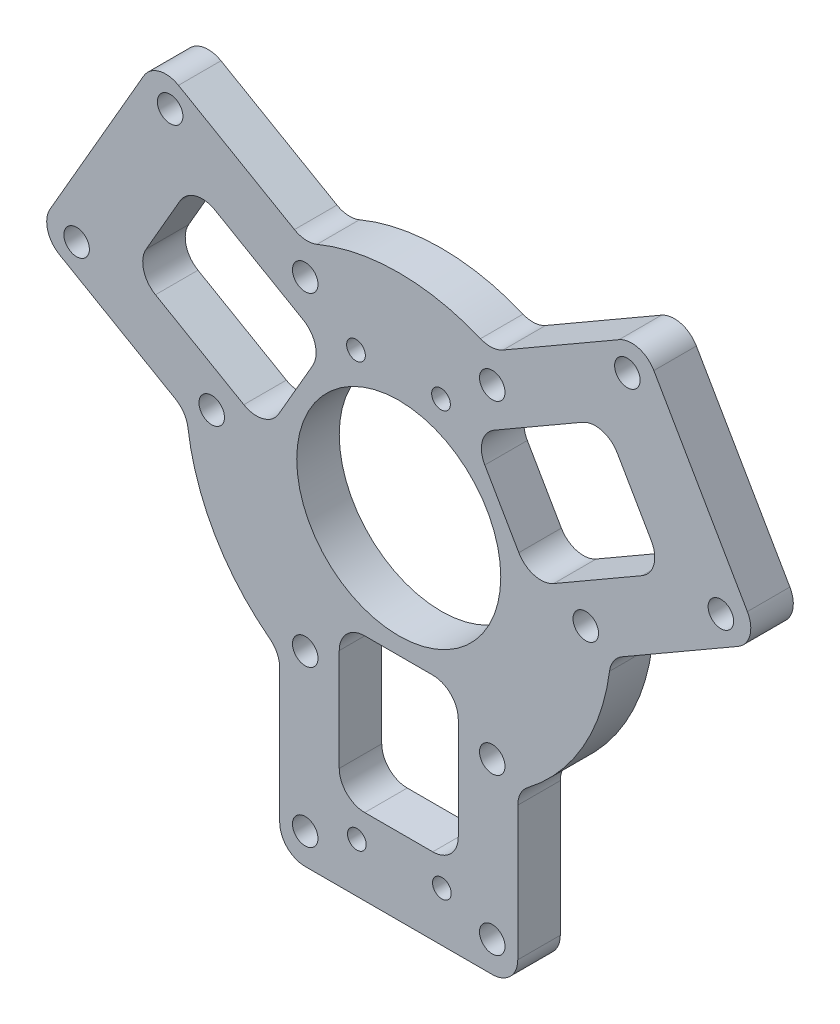
SolidWorks part; units mm, degrees
ref_plane "Front Plane" through (0, 0, 0) normal (0, 0, 1) x (1, 0, 0)
ref_plane "Top Plane" through (0, 0, 0) normal (0, 1, 0) x (1, 0, 0)
ref_plane "Right Plane" through (0, 0, 0) normal (1, 0, 0) x (0, 0, -1)
sketch "Sketch1" plane through (0, 0, 0) normal (0, 0, 1) x (1, 0, 0)
  line L0 (0, 0) -> (0, -37.7228) construction
  line L1 (-10.9374, 22.4805) -> (-28.507, 32.6244)
  line L2 (-14, -20.7123) -> (14, -20.7123) construction
  line L3 (-14, -20.7123) -> (-14, -41)
  line L4 (-14, -41) -> (14, -41)
  line L5 (14, -20.7123) -> (14, -41)
  line L6 (-14, -20.7123) -> (14, -41) construction
  line L7 (-14, -41) -> (14, -20.7123) construction
  line L8 (-28.507, 32.6244) -> (-42.507, 8.3756)
  line L9 (-24.9374, -1.7682) -> (-42.507, 8.3756)
  line L10 (24.9374, -1.7682) -> (42.507, 8.3756)
  line L11 (42.507, 8.3756) -> (28.507, 32.6244)
  line L12 (10.9374, 22.4805) -> (28.507, 32.6244)
  circle A0 centre (0, 0) radius 25
  point P3 (0, -30.8562)
  point P20 (0, 0)
  dimension "D1" = 50
  dimension "D2" = 28
  dimension "D3" = 41
  dimension "D4" = 3
extrude "Boss-Extrude1" add sketch "Sketch1" along normal blind 5 contours A0 L1 L8 L9 | A0 | A0 L10 L11 L12 | A0 L3 L4 L5
sketch "Sketch2" plane through (0, 0, 5) normal (0, 0, 1) x (1, 0, 0)
  line L0 (0, 0) -> (0, -37.4) construction
  line L1 (0, -37.4) -> (11, -37.4) construction
  line L3 (-32.3894, 18.7) -> (-37.8894, 9.1737) construction
  line L4 (32.3894, 18.7) -> (26.8894, 28.2263) construction
  circle A0 centre (11, -37.4) radius 1.5
  circle A1 centre (-11, -37.4) radius 1.5
  circle A2 centre (-37.8894, 9.1737) radius 1.5
  circle A3 centre (-26.8894, 28.2263) radius 1.5
  circle A4 centre (26.8894, 28.2263) radius 1.5
  circle A5 centre (37.8894, 9.1737) radius 1.5
  point P22 (0, 0)
  dimension "D2" = 3
  dimension "D1" = 11
  dimension "D3" = 37.4
  dimension "D4" = 3
extrude "Cut-Extrude1" cut sketch "Sketch2" against normal up to next
fillet "Fillet1" radius 3 6 edges at (42.507, 8.3756, 2.5) (28.507, 32.6244, 2.5) (-28.507, 32.6244, 2.5) (-42.507, 8.3756, 2.5) (14, -41, 2.5) (-14, -41, 2.5)
sketch "Sketch3" plane through (0, 0, 0) normal (0, 0, -1) x (-1, 0, 0)
  circle A0 centre (5.0306, 14.5957) radius 1.1
  circle A1 centre (-4.9693, 14.6167) radius 1.1
  circle A2 centre (4.9261, -35.1835) radius 1.1
  circle A3 centre (-5.0739, -35.1625) radius 1.1
  dimension "D1" = 2.2
extrude "Cut-Extrude2" cut sketch "Sketch3" against normal up to next
sketch "Sketch4" plane through (0, 0, 5) normal (0, 0, 1) x (1, 0, 0)
  line L0 (0, 0) -> (22, 0) construction
  circle A0 centre (22, 0) radius 1.5
  circle A1 centre (11, -19.0526) radius 1.5
  circle A2 centre (-11, -19.0526) radius 1.5
  circle A3 centre (-22, 0) radius 1.5
  circle A4 centre (-11, 19.0526) radius 1.5
  circle A5 centre (11, 19.0526) radius 1.5
  point P17 (0, 0)
  dimension "D2" = 3
  dimension "D1" = 22
  dimension "D3" = 6
extrude "Cut-Extrude3" cut sketch "Sketch4" against normal up to next
fillet "Fillet2" radius 3 6 edges at (-10.9374, 22.4805, 2.5) (10.9374, 22.4805, 2.5) (24.9374, -1.7682, 2.5) (14, -20.7123, 2.5) (-14, -20.7123, 2.5) (-24.9374, -1.7682, 2.5)
sketch "Sketch5" plane through (0, 0, 5) normal (0, 0, 1) x (1, 0, 0)
  line L0 (0, 0) -> (0, -34.8907) construction
  line L1 (-8.6244, 13.0622) -> (-15.6244, 0.9378)
  line L2 (-7, -32) -> (7, -32)
  line L3 (-7, -32) -> (-7, -14)
  line L4 (-7, -14) -> (7, -14)
  line L5 (7, -32) -> (7, -14)
  line L6 (-7, -32) -> (7, -14) construction
  line L7 (-7, -14) -> (7, -32) construction
  line L8 (-24.2128, 22.0622) -> (-31.2128, 9.9378)
  line L9 (-31.2128, 9.9378) -> (-15.6244, 0.9378)
  line L10 (-24.2128, 22.0622) -> (-8.6244, 13.0622)
  line L11 (15.6244, 0.9378) -> (8.6244, 13.0622)
  line L12 (31.2128, 9.9378) -> (24.2128, 22.0622)
  line L13 (24.2128, 22.0622) -> (8.6244, 13.0622)
  line L14 (31.2128, 9.9378) -> (15.6244, 0.9378)
  circle A0 centre (0, 0) radius 12
  point P3 (0, -23)
  point P20 (0, 0)
  dimension "D1" = 24
  dimension "D2" = 14
  dimension "D3" = 18
  dimension "D4" = 14
  dimension "D5" = 3
extrude "Cut-Extrude4" cut sketch "Sketch5" against normal up to next
fillet "Fillet3" radius 3 12 edges at (7, -14, 2.5) (7, -32, 2.5) (-7, -32, 2.5) (-7, -14, 2.5) (24.2128, 22.0622, 2.5) (31.2128, 9.9378, 2.5) (15.6244, 0.9378, 2.5) (8.6244, 13.0622, 2.5) (-8.6244, 13.0622, 2.5) (-15.6244, 0.9378, 2.5) (-31.2128, 9.9378, 2.5) (-24.2128, 22.0622, 2.5)
